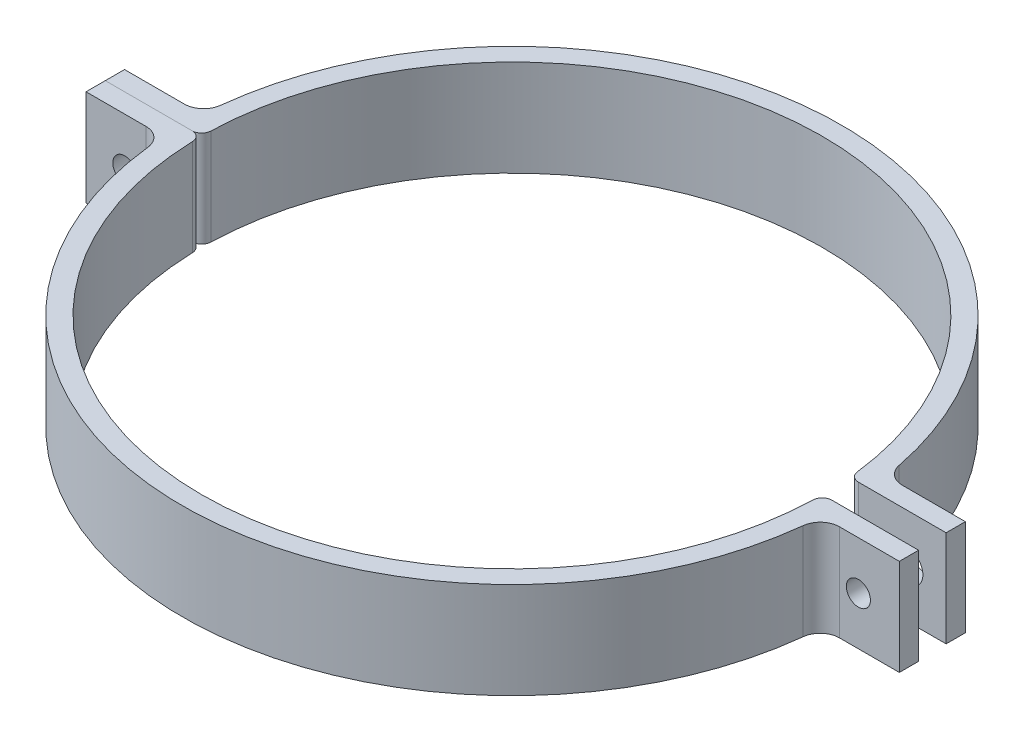
SolidWorks part; units mm, degrees
ref_plane "Спереди" through (0, 0, 0) normal (0, 0, 1) x (1, 0, 0)
ref_plane "Сверху" through (0, 0, 0) normal (0, 1, 0) x (1, 0, 0)
ref_plane "Справа" through (0, 0, 0) normal (1, 0, 0) x (0, 0, -1)
sketch "Эскиз1" plane through (0, 0, 0) normal (0, 1, 0) x (1, 0, 0)
  circle A0 centre (0, 0) radius 32.25
  circle A1 centre (0, 0) radius 34.25
  dimension "D1" = 64.5
  dimension "D2" = 2
extrude "Бобышка-Вытянуть1" add sketch "Эскиз1" along normal blind 10
split "Разделить1" trim tools "Спереди" bodies to split 103 resulting bodies 104 105
sketch "Эскиз2" plane through (0, 10, 0) normal (0, 1, 0) x (1, 0, 0)
  line L0 (32.25, 0) -> (34.25, 0) construction
  line L1 (27.7467, 3) -> (34.25, 3)
  line L2 (27.7467, 3) -> (27.7467, 0)
  line L3 (27.7467, 0) -> (34.25, 0)
  line L4 (34.25, 3) -> (34.25, 0)
  arc A0 (34.25, 0) -> (-34.25, 0) centre (0, 0) ccw construction
  dimension "D1" = 3
  dimension "D2" = 6.5033
extrude "Вырез-Вытянуть1" cut sketch "Эскиз2" against normal through all
sketch "Эскиз5" plane through (0, 0, -3) normal (0, 0, 1) x (1, 0, 0)
  line L1 (32.1102, 0) -> (42.1102, 0)
  line L2 (32.1102, 0) -> (32.1102, 10)
  line L3 (32.1102, 10) -> (42.1102, 10)
  line L4 (42.1102, 0) -> (42.1102, 10)
  line L5 (34.1184, 10) -> (32.1102, 10) construction
  dimension "D1" = 10
extrude "Бобышка-Вытянуть2" add sketch "Эскиз5" against normal blind 2
sketch "Эскиз6" plane through (0, 0, 0) normal (0, 0, 1) x (1, 0, 0)
  line L0 (-34.25, 10) -> (-32.25, 10) construction
  line L1 (-32.25, 0) -> (-42.25, 0)
  line L2 (-32.25, 0) -> (-32.25, 10)
  line L3 (-32.25, 10) -> (-42.25, 10)
  line L4 (-42.25, 0) -> (-42.25, 10)
  dimension "D1" = 10
extrude "Бобышка-Вытянуть3" add sketch "Эскиз6" against normal blind 2
sketch "Эскиз7" plane through (0, 0, -2) normal (0, 0, -1) x (-1, 0, 0)
  line L0 (38.2208, 10) -> (38.2208, 0) construction
  line L1 (34.1916, 10) -> (42.25, 10) construction
  line L2 (42.25, 0) -> (34.1916, 0) construction
  line L3 (42.25, 5) -> (34.1916, 5) construction
  line L4 (42.25, 10) -> (42.25, 0) construction
  line L5 (34.1916, 10) -> (34.1916, 0) construction
  line L6 (34.1916, 5) -> (-42.1102, 5) construction
  line L7 (-42.1102, 0) -> (-42.1102, 10) construction
  line L8 (-37.9966, 10) -> (-37.9966, 0) construction
  line L9 (-42.1102, 10) -> (-33.8831, 10) construction
  line L10 (-33.8831, 0) -> (-42.1102, 0) construction
sketch "Эскиз10" plane through (0, 0, 0) normal (0, 0, -1) x (-1, 0, 0)
  line L0 (34.25, 10) -> (32.25, 10) construction
  line L1 (32.25, 0) -> (42.25, 0)
  line L2 (32.25, 0) -> (32.25, 10)
  line L3 (32.25, 10) -> (42.25, 10)
  line L4 (42.25, 0) -> (42.25, 10)
  line L5 (-32.25, 10) -> (-34.25, 10) construction
  line L6 (-32.25, 0) -> (-42.25, 0)
  line L7 (-32.25, 0) -> (-32.25, 10)
  line L8 (-32.25, 10) -> (-42.25, 10)
  line L9 (-42.25, 0) -> (-42.25, 10)
  dimension "D1" = 10
  dimension "D2" = 10
extrude "Бобышка-Вытянуть4" add sketch "Эскиз10" against normal blind 2
hole_wizard "Отверстие с зазором M31" positions "Эскиз9" profile "Эскиз8" hole size "M3" standard "Ansi Metric" end condition through all
sketch "Эскиз9" plane through (0, 0, -5) normal (0, 0, -1) x (-1, 0, 0)
  line L0 (-37.9966, 10) -> (-37.9966, 0) construction
  line L1 (38.2208, 10) -> (38.2208, 0) construction
  point P0 (-37.9966, 5)
  point P4 (38.2208, 5)
sketch "Эскиз8" plane through (37.9966, 5, -5) normal (1, 0, 0) x (0, 1, 0)
  line L0 (0, 0) -> (0, 39.25)
  line L1 (0, 39.25) -> (1.7, 39.25)
  line L2 (1.7, 39.25) -> (1.7, 0)
  line L5 (1.7, 0) -> (0, 0)
  line L11 (0, -6.35) -> (0, 107.95) construction
  dimension "Диаметр сквозного отверстия" = 3.4
  dimension "Глубина сквозного отверстия" = 39.25
hole_wizard "Отверстие обработанное метчиком M3x0.51" positions "Эскиз12" profile "Эскиз11" tap size "M3x0.5" standard "Ansi Metric"
sketch "Эскиз12" plane through (0, 0, 2) normal (0, 0, 1) x (1, 0, 0)
  line L0 (37.9966, 10) -> (37.9966, 0) construction
  line L1 (-38.2208, 10) -> (-38.2208, 0) construction
  point P0 (37.9966, 5)
  point P4 (-38.2208, 5)
sketch "Эскиз11" plane through (37.9966, 5, 2) normal (1, 0, 0) x (0, -1, 0)
  line L0 (0, 0) -> (0, 9.2511)
  line L1 (0, 9.2511) -> (1.25, 8.5)
  line L2 (1.25, 8.5) -> (1.25, 0)
  line L5 (1.25, 0) -> (0, 0)
  line L10 (0, 9.2511) -> (-1.25, 8.5) construction
  line L11 (0, -6.35) -> (0, 107.95) construction
  dimension "Диаметр сверла" = 2.5
  dimension "Глубина сверла" = 8.5
  dimension "Угол заточки сверла" = 118
fillet "Скругление1" radius 2 2 edges at (33.8831, 5, -5) (-34.1916, 5, -2)
fillet "Скругление3" radius 1 2 edges at (32.1102, 5, -3) (-32.25, 5, 0)
fillet "Скругление4" radius 1 2 edges at (-32.25, 5, 0) (32.25, 5, 0)
fillet "Скругление5" radius 2 2 edges at (-34.1916, 5, 2) (34.1916, 5, 2)
